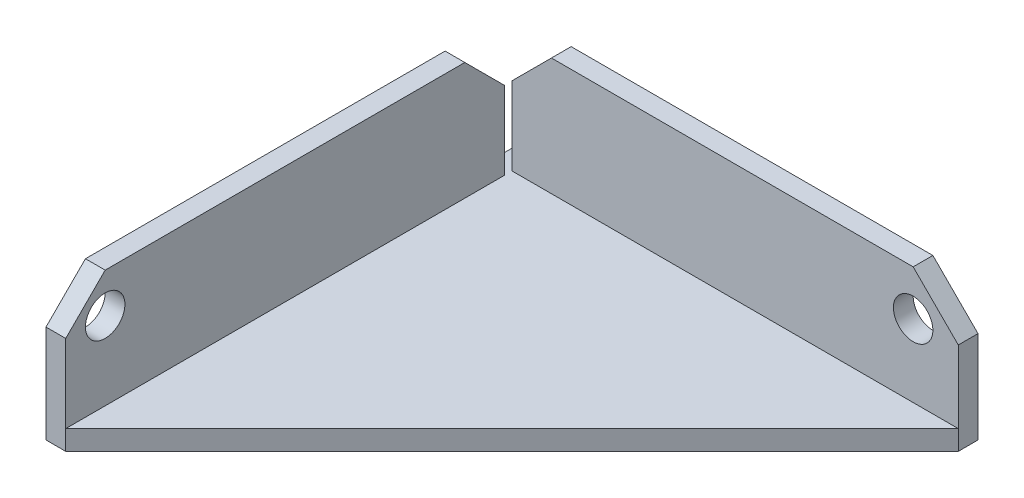
SolidWorks part; units mm, degrees
ref_plane "Front Plane" through (0, 0, 0) normal (0, 0, 1) x (1, 0, 0)
ref_plane "Top Plane" through (0, 0, 0) normal (0, 1, 0) x (1, 0, 0)
ref_plane "Right Plane" through (0, 0, 0) normal (1, 0, 0) x (0, 0, -1)
sketch "Sketch1" plane through (0, 0, 0) normal (0, 1, 0) x (1, 0, 0)
  line L0 (-16.3454, 62.1194) -> (58.6717, 62.1194)
  line L1 (58.6717, 62.1194) -> (58.6717, 58.9444)
  line L2 (58.6717, 58.9444) -> (-13.1704, -12.8976)
  line L3 (-13.1704, -12.8976) -> (-16.3454, -12.8976)
  line L4 (-16.3454, -12.8976) -> (-16.3454, 62.1194)
  dimension "D1" = 3.175
  dimension "D2" = 3.175
  dimension "D3" = 101.6
  dimension "D4" = 45
extrude "Boss-Extrude1" add sketch "Sketch1" along normal blind 3.175 contours L4 L0 L1 L2 L3
sketch "Sketch2" plane through (0, 3.175, 0) normal (0, 1, 0) x (1, 0, 0)
  line L0 (-13.1704, 58.9444) -> (-13.1704, 62.1194)
  line L1 (-13.1704, -12.8976) -> (-16.3454, -12.8976)
  line L2 (-13.1704, -12.8976) -> (-13.1704, 58.9444)
  line L4 (-16.3454, -12.8976) -> (-16.3454, 58.9444)
  line L5 (58.6717, 58.9444) -> (-13.1704, 58.9444)
  line L6 (58.6717, 58.9444) -> (58.6717, 62.1194)
  line L7 (58.6717, 62.1194) -> (-13.1704, 62.1194)
  line L9 (-13.1704, 58.9444) -> (-16.3454, 58.9444)
  line M3 (58.6717, 58.9444) -> (58.6717, 62.1194)
  line M4 (58.6717, 62.1194) -> (-16.3454, 62.1194)
extrude "Boss-Extrude2" add sketch "Sketch2" along normal blind 18.923 contours L5 L0 M3 M4 | L9 L4 L1 L2
sketch "Sketch3" plane through (0, 3.175, 0) normal (0, 1, 0) x (1, 0, 0)
  line L9 (-16.3454, -12.8976) -> (-16.3454, 62.1194) construction
  line L10 (-13.1704, -12.8976) -> (-16.3454, -12.8976)
  line L11 (-13.1704, -12.8976) -> (-13.1704, 57.7013)
  line L12 (-13.1704, 57.7013) -> (-16.3454, 57.7013)
  line L13 (-16.3454, -12.8976) -> (-16.3454, 57.7013)
extrude "Boss-Extrude6" add sketch "Sketch3" along normal blind 18.923 contours L11 L12 L13 L10
sketch "Sketch4" plane through (-16.3454, 0, 0) normal (-1, 0, 0) x (0, 0, 1)
  line L0 (6.5476, 22.098) -> (12.8976, 15.748)
  line L1 (12.8976, 22.098) -> (-57.7013, 22.098) construction
  line L2 (12.8976, 22.098) -> (12.8976, 0) construction
  line L3 (12.8976, 15.748) -> (12.8976, 22.098)
  line L4 (12.8976, 22.098) -> (6.5476, 22.098)
  line L5 (-57.7013, 22.098) -> (-57.7013, 15.748)
  line L6 (-57.7013, 22.098) -> (-57.7013, 3.175) construction
  line L7 (-57.7013, 15.748) -> (-51.3513, 22.098)
  line L8 (-51.3513, 22.098) -> (-57.7013, 22.098)
  dimension "D1" = 135
  dimension "D2" = 6.35
  dimension "D3" = 135
extrude "Cut-Extrude1" cut sketch "Sketch4" against normal blind 18.923 contours L7 L8 L5
sketch "Sketch5" plane through (0, 0, -62.1194) normal (0, 0, -1) x (-1, 0, 0)
  line L0 (13.1704, 15.748) -> (6.8204, 22.098)
  line L1 (-58.6717, 22.098) -> (13.1704, 22.098) construction
  line L2 (6.8204, 22.098) -> (13.1704, 22.098)
  line L3 (13.1704, 22.098) -> (13.1704, 15.748)
  line L4 (-58.6717, 14.8349) -> (-51.4086, 22.098)
  line L5 (-58.6717, 22.098) -> (-58.6717, 0) construction
  line L6 (-51.4086, 22.098) -> (-58.6717, 22.098)
  line L7 (-58.6717, 22.098) -> (-58.6717, 14.8349)
  dimension "D1" = 135
  dimension "D2" = 45
extrude "Cut-Extrude2" cut sketch "Sketch5" against normal blind 18.923 contours L6 L7 L4
sketch "Sketch6" plane through (0, 0, -58.9444) normal (0, 0, 1) x (1, 0, 0)
  circle A0 centre (51.4086, 14.8349) radius 3.175
  dimension "D1" = 6.35
sketch "Sketch7" plane through (-13.1704, 0, 0) normal (1, 0, 0) x (0, 0, -1)
  circle A0 centre (-6.5476, 15.748) radius 3.175
  dimension "D1" = 6.35
extrude "Cut-Extrude3" cut sketch "Sketch7" against normal blind 18.923
extrude "Cut-Extrude4" cut sketch "Sketch6" against normal blind 18.923 contours A0
